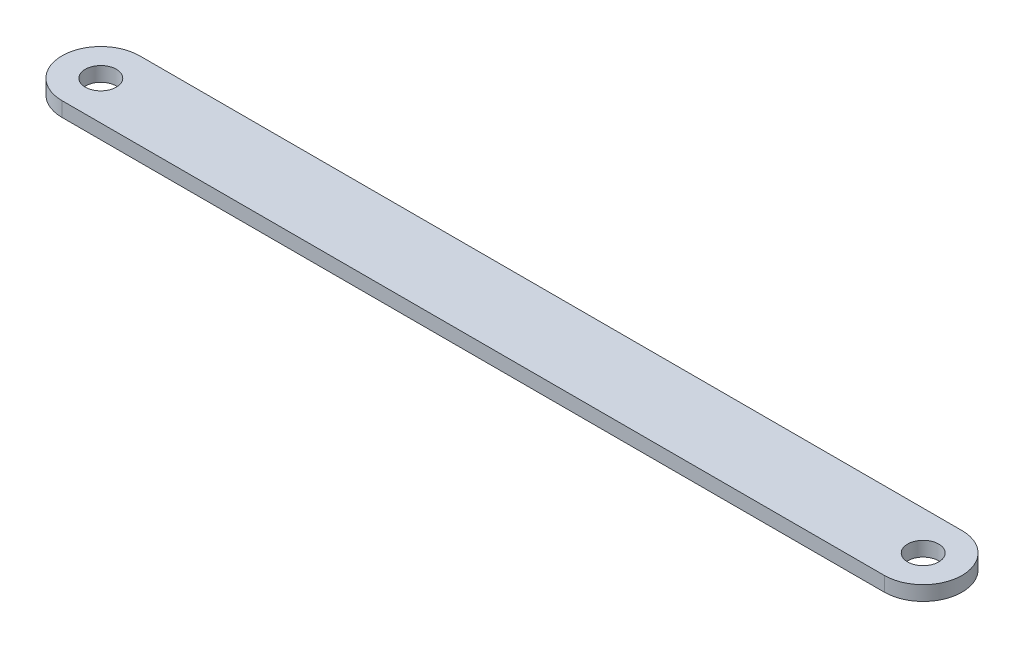
SolidWorks part; units mm, degrees
ref_plane "Front Plane" through (0, 0, 0) normal (0, 0, 1) x (1, 0, 0)
ref_plane "Top Plane" through (0, 0, 0) normal (0, 1, 0) x (1, 0, 0)
ref_plane "Right Plane" through (0, 0, 0) normal (1, 0, 0) x (0, 0, -1)
sketch "Sketch1" plane through (0, 0, 0) normal (0, 1, 0) x (1, 0, 0)
  line L0 (-42.35, 0) -> (42.35, 0) construction
  line L1 (-42.35, 4) -> (42.35, 4)
  line L2 (-42.35, -4) -> (42.35, -4)
  arc A0 (-42.35, 4) -> (-42.35, -4) centre (-42.35, 0) ccw
  arc A1 (42.35, -4) -> (42.35, 4) centre (42.35, 0) ccw
  circle A2 centre (-42.35, 0) radius 1.6
  circle A3 centre (42.35, 0) radius 1.6
  point P2 (0, 0)
  dimension "D3" = 3.2
  dimension "D1" = 8
  dimension "D2" = 84.7
extrude "Boss-Extrude1" add sketch "Sketch1" along normal blind 1.5
